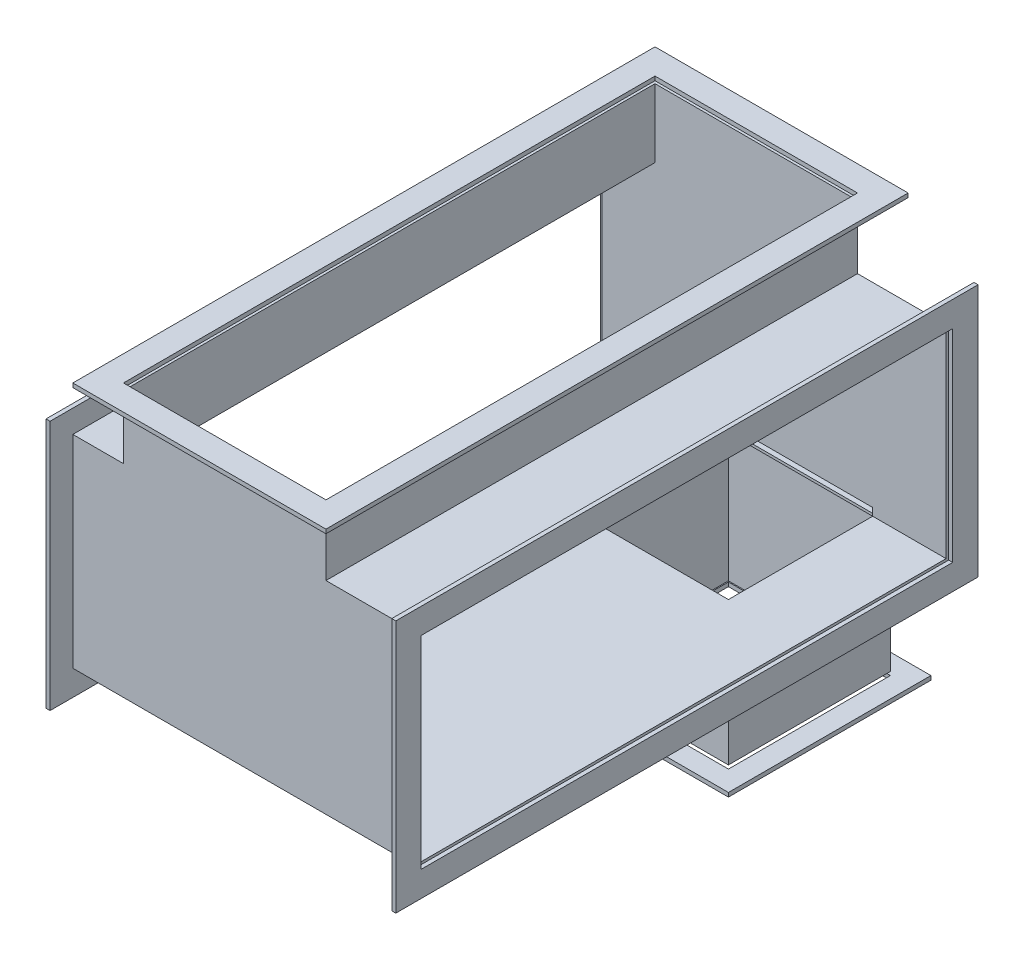
SolidWorks part; units mm, degrees
ref_plane "Front Plane" through (0, 0, 0) normal (0, 0, 1) x (1, 0, 0)
ref_plane "Top Plane" through (0, 0, 0) normal (0, 1, 0) x (1, 0, 0)
ref_plane "Right Plane" through (0, 0, 0) normal (1, 0, 0) x (0, 0, -1)
sketch "Sketch2" plane through (0, 0, 0) normal (0, 0, 1) x (1, 0, 0)
  line L0 (200, 200) -> (380, 200)
  line L1 (-300, 200) -> (-200, 200)
  line L2 (-300, 200) -> (-300, -200)
  line L3 (-300, -200) -> (-200, -200)
  line L4 (380, 200) -> (380, -200)
  line L5 (200, -200) -> (380, -200)
  line L6 (-200, -200) -> (200, -200)
  line L7 (-200, 330) -> (200, 330)
  line L8 (-200, 330) -> (-200, 200)
  line L10 (200, 330) -> (200, 200)
  point P0 (0, 0)
  point P6 (0, 0)
  dimension "D1" = 680
  dimension "D2" = 400
  dimension "D3" = 330
  dimension "D4" = 400
  dimension "D5" = 300
  dimension "D6" = 100
  dimension "D7" = 130
extrude "Boss-Extrude1" add sketch "Sketch2" along normal blind 1050
sketch "Sketch4" plane through (0, -200, 0) normal (0, -1, 0) x (1, 0, 0)
  line L0 (525.1025, 525) -> (-381.4859, 525) construction
  line L1 (240, 295) -> (-80, 295)
  line L2 (240, 295) -> (240, -25)
  line L3 (240, -25) -> (-80, -25)
  line L4 (-80, 295) -> (-80, -25)
  line L5 (240, 295) -> (-80, -25) construction
  line L6 (240, -25) -> (-80, 295) construction
  line L7 (-300, 0) -> (380, 0) construction
  line L8 (380, 1050) -> (380, 0) construction
  point P0 (80, 135)
  dimension "D1" = 525
  dimension "D2" = 390
  dimension "D3" = 320
  dimension "D4" = 320
  dimension "D5" = 300
extrude "Boss-Extrude2" add sketch "Sketch4" along normal blind 280
sketch "Sketch5" plane through (380, 0, 0) normal (1, 0, 0) x (0, 0, -1)
  line L1 (-1050, 200) -> (0, 200)
  line L2 (-1050, 200) -> (-1050, -200)
  line L3 (-1050, -200) -> (0, -200)
  line L4 (0, 200) -> (0, -200)
  line L5 (-1100, 250) -> (50, 250)
  line L6 (-1100, 250) -> (-1100, -250)
  line L7 (-1100, -250) -> (50, -250)
  line L8 (50, 250) -> (50, -250)
  dimension "D1" = 50
  dimension "D2" = 50
  dimension "D3" = 50
  dimension "D4" = 50
extrude "Boss-Extrude3" add sketch "Sketch5" along normal blind 8 separate body
sketch "Sketch6" plane through (380, 0, 0) normal (1, 0, 0) x (0, 0, -1)
  line L0 (0, 200) -> (-1050, 200) construction
  line L1 (-1045, 195) -> (-5, 195)
  line L2 (-1045, 195) -> (-1045, -195)
  line L3 (-1045, -195) -> (-5, -195)
  line L4 (-5, 195) -> (-5, -195)
  line L5 (0, -200) -> (0, 200) construction
  line L6 (-1050, -200) -> (0, -200) construction
  line L7 (-1050, 200) -> (-1050, -200) construction
  dimension "D1" = 5
  dimension "D2" = 5
  dimension "D3" = 5
  dimension "D4" = 5
extrude "Cut-Extrude1" cut sketch "Sketch6" against normal blind 690
sketch "Sketch7" plane through (0, 330, 0) normal (0, 1, 0) x (1, 0, 0)
  line L1 (-200, 0) -> (200, 0)
  line L2 (-200, 0) -> (-200, -1050)
  line L3 (-200, -1050) -> (200, -1050)
  line L4 (200, 0) -> (200, -1050)
  line L5 (-250, 50) -> (250, 50)
  line L6 (-250, 50) -> (-250, -1100)
  line L7 (-250, -1100) -> (250, -1100)
  line L8 (250, 50) -> (250, -1100)
  dimension "D1" = 50
  dimension "D2" = 50
  dimension "D3" = 50
  dimension "D4" = 50
extrude "Boss-Extrude4" add sketch "Sketch7" along normal blind 8 separate body
sketch "Sketch11" plane through (-300, 0, 0) normal (-1, 0, 0) x (0, 0, 1)
  line L0 (5, 195) -> (1045, 195) construction
  line L1 (0, 200) -> (1045, 200)
  line L2 (0, 200) -> (0, -195)
  line L3 (0, -195) -> (1045, -195)
  line L4 (1045, 200) -> (1045, -195)
  line L5 (-50, 245) -> (1095, 245)
  line L6 (-50, 245) -> (-50, -250)
  line L7 (-50, -250) -> (1095, -250)
  line L8 (1095, 245) -> (1095, -250)
  line L9 (1050, -200) -> (0, -200) construction
  dimension "D1" = 50
  dimension "D2" = 50
  dimension "D3" = 50
  dimension "D4" = 50
extrude "Boss-Extrude8" add sketch "Sketch11" along normal blind 8 separate body
sketch "Sketch12" plane through (0, 330, 0) normal (0, 1, 0) x (1, 0, 0)
  line L0 (200, 0) -> (-200, 0) construction
  line L1 (-195, -5) -> (195, -5)
  line L2 (-195, -5) -> (-195, -1045)
  line L3 (-195, -1045) -> (195, -1045)
  line L4 (195, -5) -> (195, -1045)
  line L5 (200, -1050) -> (200, 0) construction
  line L7 (200, -1050) -> (-200, -1050) construction
  line L8 (-200, -1050) -> (-200, 0) construction
  dimension "D1" = 5
  dimension "D2" = 5
  dimension "D3" = 5
  dimension "D4" = 5
extrude "Cut-Extrude4" cut sketch "Sketch12" against normal blind 300
sketch "Sketch14" plane through (0, -480, 0) normal (0, -1, 0) x (-1, 0, 0)
  line L0 (-240, -295) -> (80, -295) construction
  line L1 (75, -290) -> (-235, -290)
  line L2 (75, -290) -> (75, 20)
  line L3 (75, 20) -> (-235, 20)
  line L4 (-235, -290) -> (-235, 20)
  line L5 (80, 25) -> (-240, 25) construction
  line L6 (-240, 25) -> (-240, -295) construction
  line L7 (80, -295) -> (80, 0) construction
  dimension "D1" = 5
  dimension "D2" = 5
  dimension "D3" = 5
  dimension "D4" = 5
extrude "Cut-Extrude5" cut sketch "Sketch14" against normal blind 300 and the other way through all
sketch "Sketch15" plane through (0, -480, 0) normal (0, -1, 0) x (-1, 0, 0)
  line L0 (-240, -295) -> (80, -295) construction
  line L1 (120, -335) -> (-280, -335)
  line L2 (120, -335) -> (120, 65)
  line L3 (120, 65) -> (-280, 65)
  line L4 (-280, -335) -> (-280, 65)
  line L5 (-240, 0) -> (-240, -295) construction
  line L6 (80, 25) -> (-240, 25) construction
  line L7 (80, -295) -> (80, 0) construction
  dimension "D1" = 40
  dimension "D2" = 40
  dimension "D3" = 40
  dimension "D4" = 40
extrude "Boss-Extrude9" add sketch "Sketch15" along normal blind 8
sketch "Sketch17" plane through (0, -200, 0) normal (0, 1, 0) x (1, 0, 0)
  line L0 (-300, -1095) -> (-300, 50) construction
  line L1 (380, 0) -> (-300, 0)
  line L2 (380, 0) -> (380, 40)
  line L3 (380, 40) -> (-300, 40)
  line L4 (-300, 0) -> (-300, 40)
  dimension "D1" = 40
extrude "Boss-Extrude13" add sketch "Sketch17" along normal blind 5 separate body
sketch "Sketch18" plane through (0, -488, 0) normal (0, -1, 0) x (1, 0, 0)
  line L0 (280, 335) -> (-120, 335) construction
  line L1 (-80, 295) -> (240, 295)
  line L2 (-80, 295) -> (-80, -25)
  line L3 (-80, -25) -> (240, -25)
  line L4 (240, 295) -> (240, -25)
  line L5 (280, -65) -> (280, 335) construction
  line L6 (-120, -65) -> (280, -65) construction
  line L7 (-120, 335) -> (-120, -65) construction
  dimension "D1" = 40
  dimension "D2" = 40
  dimension "D3" = 40
  dimension "D4" = 40
extrude "Cut-Extrude6" cut sketch "Sketch18" against normal blind 15
